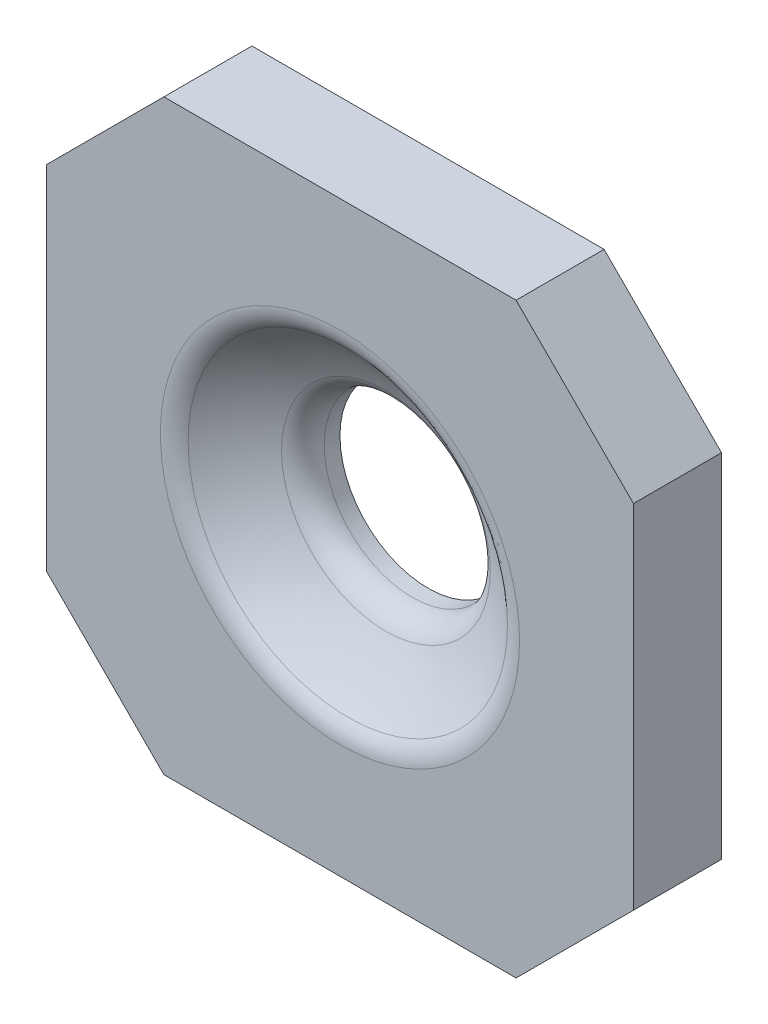
SolidWorks part; units mm, degrees
material "ﾎﾟﾘｴﾁﾚﾝ(PE)高密度"
ref_plane "正面" through (0, 0, 0) normal (0, 0, 1) x (1, 0, 0)
ref_plane "平面" through (0, 0, 0) normal (0, 1, 0) x (1, 0, 0)
ref_plane "右側面" through (0, 0, 0) normal (1, 0, 0) x (0, 0, -1)
sketch "ｽｹｯﾁ2" plane through (0, 0, 0) normal (0, 0, 1) x (1, 0, 0)
  line L1 (-50, 50) -> (50, 50)
  line L2 (-50, 50) -> (-50, -50)
  line L3 (-50, -50) -> (50, -50)
  line L4 (50, 50) -> (50, -50)
  line L5 (-50, 50) -> (50, -50) construction
  line L6 (-50, -50) -> (50, 50) construction
  dimension "D2" = 100
extrude "ﾎﾞｽ - 押し出し1" add sketch "ｽｹｯﾁ2" along normal blind 15
sketch "ｽｹｯﾁ3" plane through (0, 0, 0) normal (0, 1, 0) x (1, 0, 0)
  line L0 (0, -83) -> (0, -3)
  arc A0 (0, -3) -> (0, -83) centre (0, -43) cw
  dimension "D2" = 40
  dimension "D1" = 3
revolve "ｶｯﾄ - 回転1" cut sketch "ｽｹｯﾁ3" angle 360 about L0
sketch "Sketch3" plane through (0, 0, 0) normal (0, 0, -1) x (-1, 0, 0)
  circle A0 centre (0, 0) radius 15
  dimension "D1" = 30
extrude "Cut-Extrude1" cut sketch "Sketch3" against normal through all
chamfer "面取り1" distance 20 angle 45 4 edges at (-50, 50, 7.5) (50, 50, 7.5) (50, -50, 7.5) (-50, -50, 7.5)
fillet "Fillet1" radius 5 1 edges at (15, 0, 5.919)
fillet "ﾌｨﾚｯﾄ1" radius 5 1 edges at (28.5657, 0, 15)
